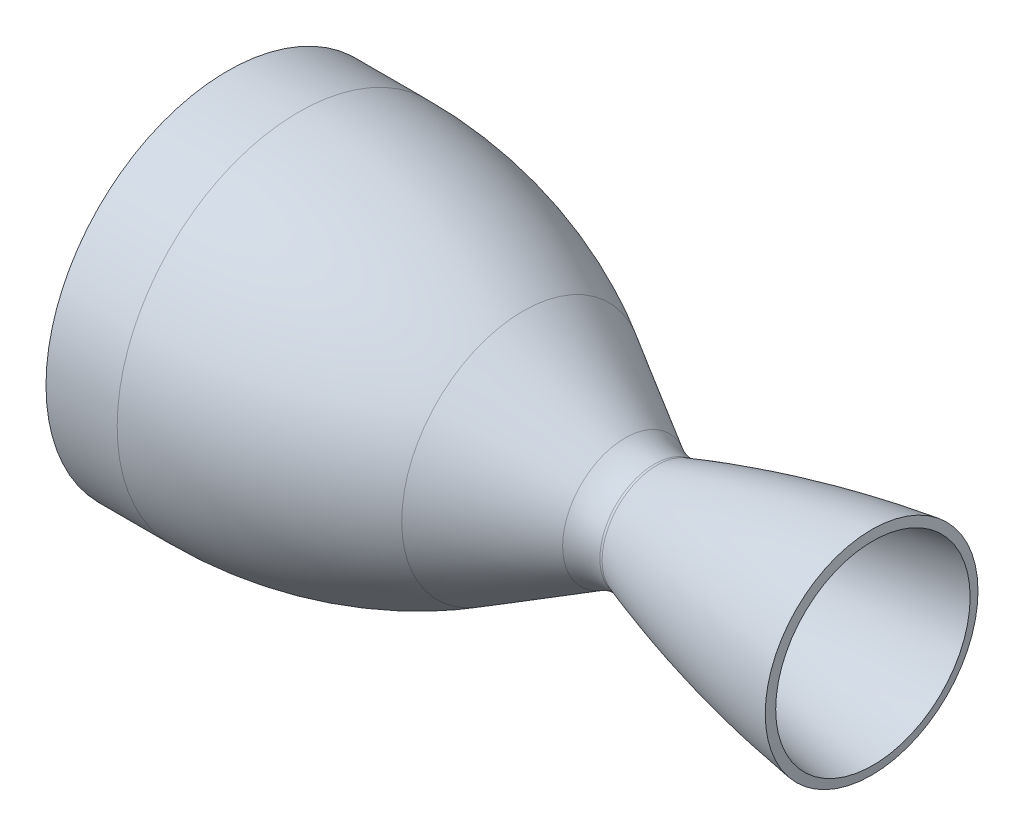
SolidWorks part; units mm, degrees
ref_plane "Front Plane" through (0, 0, 0) normal (0, 0, 1) x (1, 0, 0)
ref_plane "Top Plane" through (0, 0, 0) normal (0, 1, 0) x (1, 0, 0)
ref_plane "Right Plane" through (0, 0, 0) normal (1, 0, 0) x (0, 0, -1)
sketch "Model" plane through (0, 0, 0) normal (0, 0, 1) x (1, 0, 0)
  line L0 (0, 94.6788) -> (39.1107, 94.6788)
  line L1 (0, 99.7588) -> (39.1107, 99.7588)
  line L2 (159.903, 62.3126) -> (215.9628, 29.9464)
  line L3 (162.443, 66.712) -> (218.5028, 34.3458)
  line L4 (0, 0) -> (354.6796, 0) construction
  line L5 (0, 99.7588) -> (0, 94.6788)
  line L6 (353.9726, 58.4606) -> (354.6796, 53.43)
  arc A0 (159.903, 62.3126) -> (39.1107, 94.6788) centre (39.1107, -146.9057) ccw
  arc A1 (162.443, 66.712) -> (39.1107, 99.7588) centre (39.1107, -146.9057) ccw
  arc A2 (215.9628, 29.9464) -> (234.6643, 24.9354) centre (234.6643, 62.3384) ccw
  arc A3 (218.5028, 34.3458) -> (234.6643, 30.0154) centre (234.6643, 62.3384) ccw
  arc A4 (234.6643, 24.9354) -> (237.7572, 25.4515) centre (234.6643, 34.4607) ccw
  arc A5 (234.6643, 30.0154) -> (236.1077, 30.2562) centre (234.6643, 34.4607) ccw
  spline S0 degree 2 poles (237.7572, 25.4515) (294.7005, 45.0005) (354.6796, 53.43) knots 0 0 0 1 1 1
  spline S1 degree 1 poles (236.1077, 30.2562) (353.9726, 58.4606) knots 0 0 1 1 construction
  spline S2 degree 2 poles (236.1077, 30.2562) (293.5143, 49.9639) (353.9726, 58.4606) knots 0 0 0 1 1 1
  dimension "D2" = 99.7588
  dimension "D3" = 354.6796
  dimension "D1" = 5.08
revolve "Revolve1" add sketch "Model" angle 360 about L4
